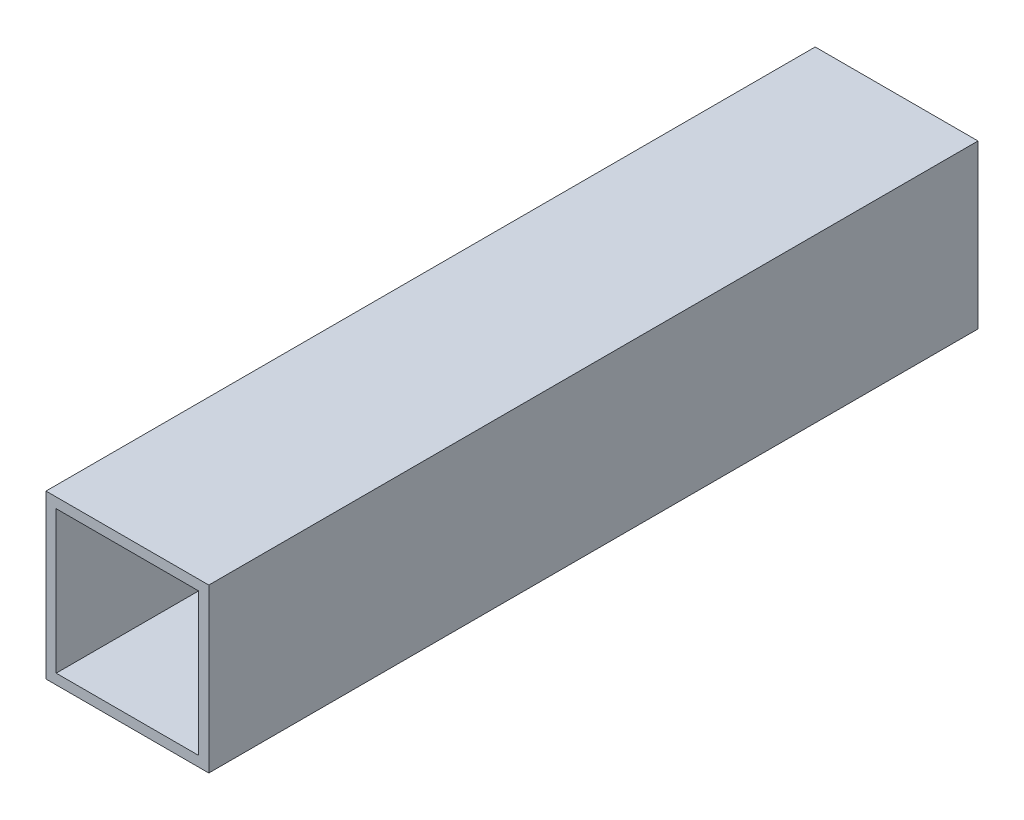
SolidWorks part; units mm, degrees
ref_plane "Front Plane" through (0, 0, 0) normal (0, 0, 1) x (1, 0, 0)
ref_plane "Top Plane" through (0, 0, 0) normal (0, 1, 0) x (1, 0, 0)
ref_plane "Right Plane" through (0, 0, 0) normal (1, 0, 0) x (0, 0, -1)
sketch "Sketch1" plane through (0, 0, 0) normal (0, 0, 1) x (1, 0, 0)
  line L1 (-11.1125, -11.1125) -> (11.1125, -11.1125)
  line L2 (-11.1125, -11.1125) -> (-11.1125, 11.1125)
  line L3 (-11.1125, 11.1125) -> (11.1125, 11.1125)
  line L4 (11.1125, -11.1125) -> (11.1125, 11.1125)
  line L5 (-11.1125, -11.1125) -> (11.1125, 11.1125) construction
  line L6 (-11.1125, 11.1125) -> (11.1125, -11.1125) construction
  line L7 (-12.7, -12.7) -> (12.7, -12.7)
  line L8 (-12.7, -12.7) -> (-12.7, 12.7)
  line L9 (-12.7, 12.7) -> (12.7, 12.7)
  line L10 (12.7, -12.7) -> (12.7, 12.7)
  line L11 (-12.7, -12.7) -> (12.7, 12.7) construction
  line L12 (-12.7, 12.7) -> (12.7, -12.7) construction
  point P0 (0, 0)
  point P6 (0, 0)
  dimension "D1" = 25.4
  dimension "D2" = 1.5875
extrude "Boss-Extrude1" add sketch "Sketch1" along normal blind 120
